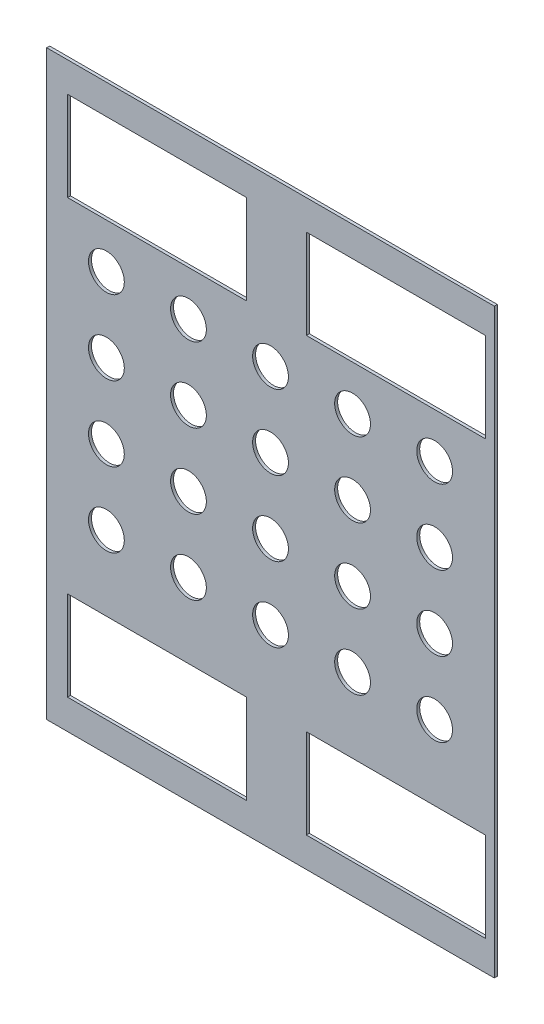
SolidWorks part; units mm, degrees
material "Rubber"
ref_plane "Front Plane" through (0, 0, 0) normal (0, 0, 1) x (1, 0, 0)
ref_plane "Top Plane" through (0, 0, 0) normal (0, 1, 0) x (1, 0, 0)
ref_plane "Right Plane" through (0, 0, 0) normal (1, 0, 0) x (0, 0, -1)
sketch "Sketch1" plane through (0, 0, 0) normal (0, 0, 1) x (1, 0, 0)
  line L1 (155.104, 174.6613) -> (5.104, 174.6613)
  line L2 (155.104, 174.6613) -> (155.104, -20.3387)
  line L3 (155.104, -20.3387) -> (5.104, -20.3387)
  line L4 (5.104, 174.6613) -> (5.104, -20.3387)
  line L6 (12.104, 164.6613) -> (72.104, 164.6613)
  line L7 (12.104, 164.6613) -> (12.104, 134.6613)
  line L8 (12.104, 134.6613) -> (72.104, 134.6613)
  line L9 (72.104, 164.6613) -> (72.104, 134.6613)
  line L10 (92.104, 164.6613) -> (152.104, 164.6613)
  line L11 (92.104, 164.6613) -> (92.104, 134.6613)
  line L12 (92.104, 134.6613) -> (152.104, 134.6613)
  line L13 (152.104, 164.6613) -> (152.104, 134.6613)
  line L14 (12.104, 19.6613) -> (72.104, 19.6613)
  line L15 (12.104, 19.6613) -> (12.104, -10.3387)
  line L16 (12.104, -10.3387) -> (72.104, -10.3387)
  line L17 (72.104, 19.6613) -> (72.104, -10.3387)
  line L18 (92.104, 19.6613) -> (152.104, 19.6613)
  line L19 (92.104, 19.6613) -> (92.104, -10.3387)
  line L20 (92.104, -10.3387) -> (152.104, -10.3387)
  line L21 (152.104, 19.6613) -> (152.104, -10.3387)
  point P4 (12.104, 149.6613)
  point P5 (122.104, 164.6613)
  point P6 (122.104, -10.3387)
  point P11 (152.104, 149.6613)
  point P12 (12.104, 4.6613)
  point P17 (152.104, 4.6613)
  dimension "D1" = 150
  dimension "D2" = 33
  dimension "D3" = 33
  dimension "D4" = 25
  dimension "D5" = 25
  dimension "D6" = 30
  dimension "D7" = 60
  dimension "D8" = 60
  dimension "D9" = 195
  dimension "D10" = 25
  dimension "D11" = 25
  dimension "D12" = 30
  dimension "D13" = 60
  dimension "D14" = 60
extrude "Boss-Extrude1" add sketch "Sketch1" along normal blind 1
sketch "Sketch2" plane through (0, 0, 1) normal (0, 0, 1) x (1, 0, 0)
  line L0 (5.104, 174.6613) -> (5.104, -20.3387) construction
  line L1 (12.104, 134.6613) -> (72.104, 134.6613) construction
  circle A0 centre (25.104, 119.6613) radius 6
  circle A1 centre (25.104, 94.6613) radius 6
  circle A2 centre (25.104, 69.6613) radius 6
  circle A3 centre (25.104, 44.6613) radius 6
  circle A4 centre (52.604, 119.6613) radius 6
  circle A5 centre (52.604, 69.6613) radius 6
  circle A6 centre (52.604, 94.6613) radius 6
  circle A7 centre (52.604, 44.6613) radius 6
  circle A8 centre (80.104, 119.6613) radius 6
  circle A9 centre (80.104, 69.6613) radius 6
  circle A10 centre (80.104, 94.6613) radius 6
  circle A11 centre (80.104, 44.6613) radius 6
  circle A12 centre (107.604, 119.6613) radius 6
  circle A13 centre (107.604, 69.6613) radius 6
  circle A14 centre (107.604, 94.6613) radius 6
  circle A15 centre (107.604, 44.6613) radius 6
  circle A16 centre (135.104, 119.6613) radius 6
  circle A17 centre (135.104, 69.6613) radius 6
  circle A18 centre (135.104, 94.6613) radius 6
  circle A19 centre (135.104, 44.6613) radius 6
  dimension "D1" = 12
  dimension "D2" = 12
  dimension "D3" = 12
  dimension "D4" = 12
  dimension "D5" = 20
  dimension "D6" = 20
  dimension "D7" = 20
  dimension "D8" = 20
  dimension "D9" = 25
  dimension "D10" = 25
  dimension "D11" = 25
  dimension "D12" = 15
  dimension "D13" = 5
extrude "Cut-Extrude1" cut sketch "Sketch2" against normal blind 2
